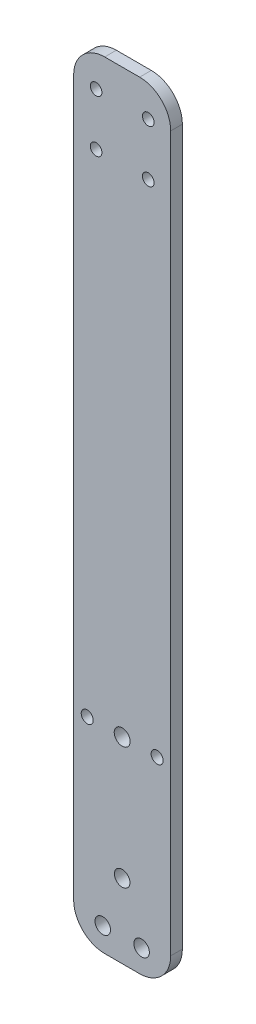
SolidWorks part; units mm, degrees
ref_plane "前视基准面" through (0, 0, 0) normal (0, 0, 1) x (1, 0, 0)
ref_plane "上视基准面" through (0, 0, 0) normal (0, 1, 0) x (1, 0, 0)
ref_plane "右视基准面" through (0, 0, 0) normal (1, 0, 0) x (0, 0, -1)
other "Configuration Table"
sketch "草图1" plane through (0, 0, 0) normal (0, 0, 1) x (1, 0, 0)
  line L0 (12.5, 0) -> (12.5, 86.1179) construction
  line L1 (0, 0) -> (25, 0)
  line L2 (0, 0) -> (0, 200)
  line L3 (0, 200) -> (25, 200)
  line L4 (25, 0) -> (25, 200)
  circle A0 centre (7.5, 6) radius 2
  circle A1 centre (17.5, 6) radius 2
  circle A2 centre (12.5, 19.0553) radius 2
  circle A3 centre (12.5, 185) radius 9.5 construction
  circle A4 centre (5.7825, 178.2825) radius 1.5
  circle A5 centre (5.7825, 191.7175) radius 1.5
  circle A6 centre (19.2175, 191.7175) radius 1.5
  circle A7 centre (19.2175, 178.2825) radius 1.5
  circle A8 centre (12.5, 50.5628) radius 2.05
  point P11 (12.5, 0)
  point P20 (12.5, 185)
  point P27 (12.5, 185)
  dimension "D1" = 4
  dimension "D7" = 19
  dimension "D9" = 3
  dimension "D11" = 4.1
  dimension "D12" = 31.5075
  dimension "D2" = 10
  dimension "D3" = 25
  dimension "D4" = 200
  dimension "D5" = 6
  dimension "D6" = 13.98
  dimension "D8" = 15
  dimension "D10" = 4
extrude "凸台-拉伸1" add sketch "草图1" along normal blind 3
fillet "圆角1" radius 8 4 edges at (25, 0, 1.5) (0, 0, 1.5) (0, 200, 1.5) (25, 200, 1.5)
sketch "草图2" plane through (0, 0, 3) normal (0, 0, 1) x (1, 0, 0)
  line L0 (19.2175, 191.7175) -> (5.7825, 178.2825) construction
  line L1 (5.7825, 191.7175) -> (19.2175, 178.2825) construction
  circle A0 centre (12.5, 185) radius 1.3164
  point P11 (12.5, 185)
sketch "草图3" plane through (0, 0, 3) normal (0, 0, 1) x (1, 0, 0)
  line L0 (12.5, 50.5628) -> (12.5, 60.55) construction
  line L1 (12.5, 50.5628) -> (23.7297, 50.5628) construction
  circle A0 centre (21.5, 50.5628) radius 1.55
  circle A1 centre (3.5, 50.5628) radius 1.55
  point P5 (22.3552, 50.5628)
  dimension "D1" = 3.1
  dimension "D2" = 18
extrude "切除-拉伸1" cut sketch "草图3" against normal up to next
